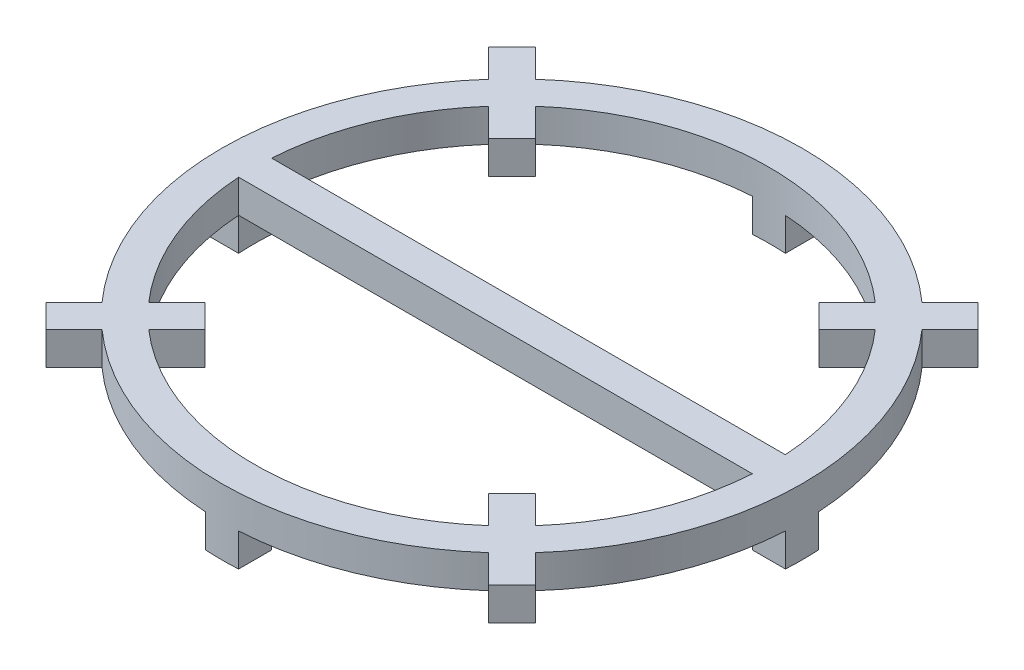
SolidWorks part; units mm, degrees
ref_plane "Front Plane" through (0, 0, 0) normal (0, 0, 1) x (1, 0, 0)
ref_plane "Top Plane" through (0, 0, 0) normal (0, 1, 0) x (1, 0, 0)
ref_plane "Right Plane" through (0, 0, 0) normal (1, 0, 0) x (0, 0, -1)
sketch "Sketch1" plane through (0, 0, 0) normal (0, 1, 0) x (1, 0, 0)
  line L0 (-38.9198, 2.5) -> (38.9198, 2.5)
  line L1 (-57.6179, 0) -> (0, 0) construction
  line L2 (0, 0) -> (-2.5, 2.5)
  line L3 (38.9198, -2.5) -> (-38.9198, -2.5)
  line L4 (-35.3051, 35.3051) -> (-37.0728, 33.5373)
  line L5 (-37.0728, 33.5373) -> (-32.8302, 29.2947)
  line L6 (-25.0456, 21.51) -> (-21.51, 25.0456)
  line L7 (-21.51, 25.0456) -> (-25.7527, 29.2882)
  line L8 (-33.5373, 37.0728) -> (-35.3051, 35.3051)
  line L9 (-29.2947, 32.8302) -> (-33.5373, 37.0728)
  line L10 (-29.2882, 25.7527) -> (-25.0456, 21.51)
  line L11 (32.8302, 29.2947) -> (37.0728, 33.5373)
  line L12 (37.0728, 33.5373) -> (35.3051, 35.3051)
  line L13 (35.3051, 35.3051) -> (33.5373, 37.0728)
  line L14 (33.5373, 37.0728) -> (29.2947, 32.8302)
  line L15 (21.51, 25.0456) -> (25.0456, 21.51)
  line L16 (25.7527, 29.2882) -> (21.51, 25.0456)
  line L17 (25.0456, 21.51) -> (29.2882, 25.7527)
  line L18 (29.2947, -32.8302) -> (33.5373, -37.0728)
  line L19 (33.5373, -37.0728) -> (35.3051, -35.3051)
  line L20 (35.3051, -35.3051) -> (37.0728, -33.5373)
  line L21 (37.0728, -33.5373) -> (32.8302, -29.2947)
  line L22 (25.0456, -21.51) -> (21.51, -25.0456)
  line L23 (29.2882, -25.7527) -> (25.0456, -21.51)
  line L24 (21.51, -25.0456) -> (25.7527, -29.2882)
  line L25 (-32.8302, -29.2947) -> (-37.0728, -33.5373)
  line L26 (-37.0728, -33.5373) -> (-35.3051, -35.3051)
  line L27 (-35.3051, -35.3051) -> (-33.5373, -37.0728)
  line L28 (-33.5373, -37.0728) -> (-29.2947, -32.8302)
  line L29 (-21.51, -25.0456) -> (-25.0456, -21.51)
  line L30 (-25.7527, -29.2882) -> (-21.51, -25.0456)
  line L31 (-25.0456, -21.51) -> (-29.2882, -25.7527)
  arc A0 (-32.8302, 29.2947) -> (-32.8302, -29.2947) centre (0, 0) ccw
  arc A1 (-38.9198, -2.5) -> (-29.2882, -25.7527) centre (0, 0) ccw
  arc A2 (38.9198, 2.5) -> (29.2882, 25.7527) centre (0, 0) ccw
  arc A3 (-29.2882, 25.7527) -> (-38.9198, 2.5) centre (0, 0) ccw
  arc A4 (25.7527, 29.2882) -> (-25.7527, 29.2882) centre (0, 0) ccw
  arc A5 (29.2947, 32.8302) -> (-29.2947, 32.8302) centre (0, 0) ccw
  arc A6 (29.2882, -25.7527) -> (38.9198, -2.5) centre (0, 0) ccw
  arc A7 (32.8302, -29.2947) -> (32.8302, 29.2947) centre (0, 0) ccw
  arc A8 (-25.7527, -29.2882) -> (25.7527, -29.2882) centre (0, 0) ccw
  arc A9 (-29.2947, -32.8302) -> (29.2947, -32.8302) centre (0, 0) ccw
  point P48 (0, 0)
  dimension "D1" = 78
  dimension "D2" = 88
  dimension "D3" = 2.5
  dimension "D4" = 2.5
  dimension "D5" = 45
  dimension "D6" = 2.5
  dimension "D7" = 2.5
  dimension "D8" = 6
  dimension "D9" = 6
  dimension "D10" = 4
extrude "Boss-Extrude1" add sketch "Sketch1" along normal blind 5
sketch "Sketch2" plane through (0, 0, 0) normal (0, -1, 0) x (1, 0, 0)
  line L0 (0, 0) -> (0, 59.9138) construction
  line L1 (-38.9198, 2.5) -> (-43.9289, 2.5)
  line L2 (-38.9198, -2.5) -> (38.9198, -2.5) construction
  line L3 (-38.9198, -2.5) -> (-43.9289, -2.5)
  line L4 (-48.1492, 0) -> (19.1329, 0) construction
  line L5 (-2.5, 38.9198) -> (-2.5, 43.9289)
  line L6 (2.5, 43.9289) -> (2.5, 38.9198)
  line L7 (38.9198, -2.5) -> (43.9289, -2.5)
  line L8 (38.9198, 2.5) -> (43.9289, 2.5)
  line L9 (2.5, -43.9289) -> (2.5, -38.9198)
  line L10 (-2.5, -38.9198) -> (-2.5, -43.9289)
  arc A0 (-43.9289, 2.5) -> (-43.9289, -2.5) centre (0, 0) ccw
  circle A1 centre (0, 0) radius 44 construction
  arc A2 (-38.9198, 2.5) -> (-38.9198, -2.5) centre (0, 0) ccw
  arc A4 (38.9198, 2.5) -> (-38.9198, 2.5) centre (0, 0) ccw construction
  arc A5 (-2.5, 38.9198) -> (2.5, 38.9198) centre (0, 0) cw
  arc A6 (-2.5, 43.9289) -> (2.5, 43.9289) centre (0, 0) cw
  arc A7 (38.9198, 2.5) -> (38.9198, -2.5) centre (0, 0) cw
  arc A8 (43.9289, 2.5) -> (43.9289, -2.5) centre (0, 0) cw
  arc A9 (-2.5, -43.9289) -> (2.5, -43.9289) centre (0, 0) ccw
  arc A10 (-2.5, -38.9198) -> (2.5, -38.9198) centre (0, 0) ccw
  dimension "D1" = 2.5
  dimension "D2" = 2.5
  dimension "D3" = 2.5
extrude "Boss-Extrude2" add sketch "Sketch2" along normal blind 5
